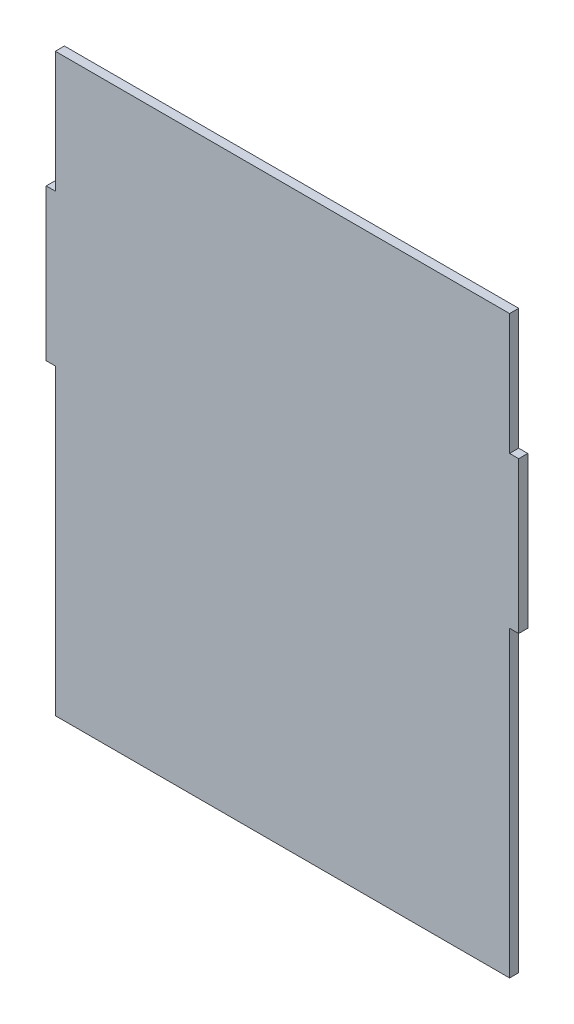
SolidWorks part; units mm, degrees
ref_plane "Alzado" through (0, 0, 0) normal (0, 0, 1) x (1, 0, 0)
ref_plane "Planta" through (0, 0, 0) normal (0, 1, 0) x (1, 0, 0)
ref_plane "Vista lateral" through (0, 0, 0) normal (1, 0, 0) x (0, 0, -1)
sketch "Croquis1" plane through (0, 0, 0) normal (0, 0, 1) x (1, 0, 0)
  line L0 (0, 150) -> (0, 190)
  line L1 (0, 0) -> (150, 0)
  line L2 (0, 0) -> (0, 100)
  line L3 (0, 190) -> (150, 190)
  line L4 (150, 0) -> (150, 100)
  line L5 (-3, 150) -> (0, 150)
  line L6 (-3, 150) -> (-3, 100)
  line L7 (-3, 100) -> (0, 100)
  line L9 (150, 150) -> (153, 150)
  line L11 (150, 100) -> (153, 100)
  line L12 (153, 150) -> (153, 100)
  line L13 (150, 150) -> (150, 190)
  dimension "D1" = 150
  dimension "D2" = 190
  dimension "D3" = 50
  dimension "D4" = 50
  dimension "D5" = 100
  dimension "D6" = 100
  dimension "D7" = 3
  dimension "D8" = 3
extrude "Saliente-Extruir1" add sketch "Croquis1" along normal blind 3
